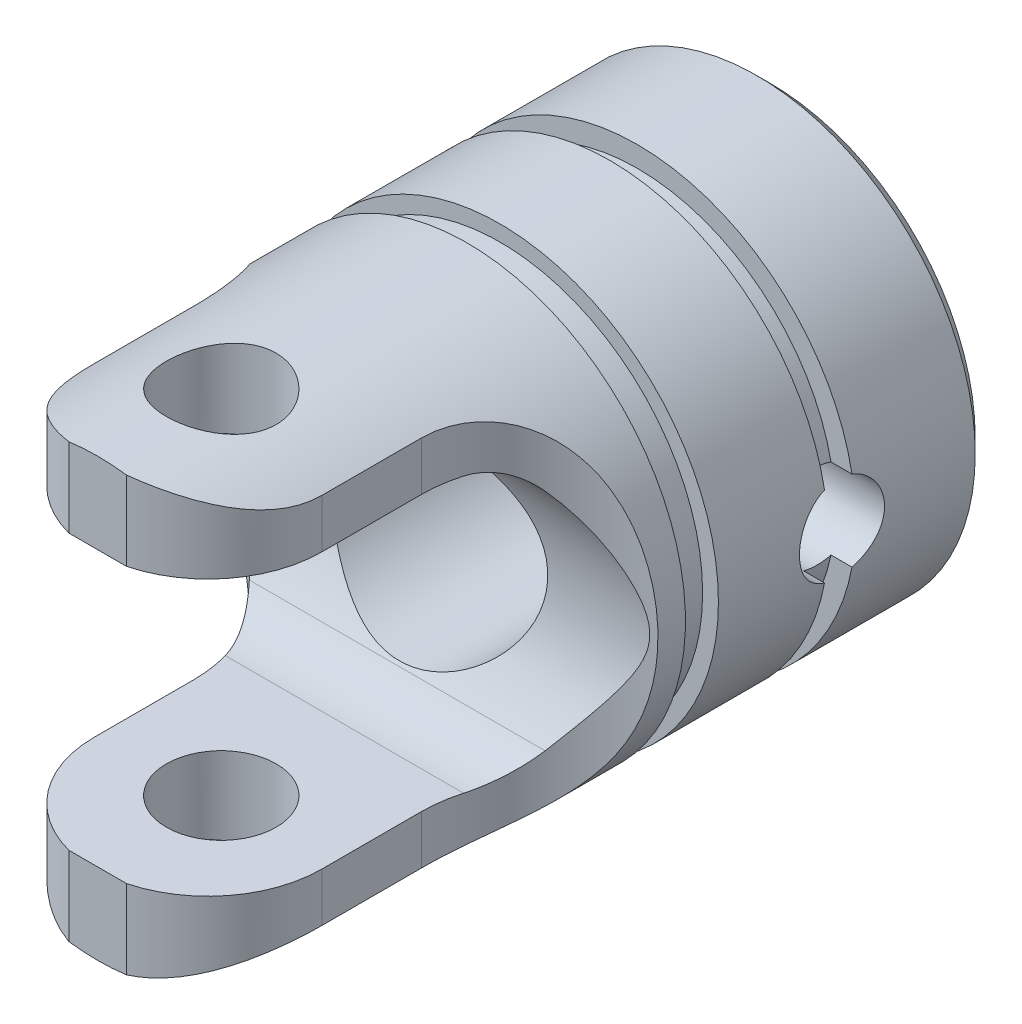
SolidWorks part; units mm, degrees
material "AISI 1020"
ref_plane "Front Plane" through (0, 0, 0) normal (0, 0, 1) x (1, 0, 0)
ref_plane "Top Plane" through (0, 0, 0) normal (0, 1, 0) x (1, 0, 0)
ref_plane "Right Plane" through (0, 0, 0) normal (1, 0, 0) x (0, 0, -1)
sketch "Sketch1" plane through (0, 0, 0) normal (0, 0, 1) x (1, 0, 0)
  circle A1 centre (0, 0) radius 15.9
  dimension "D1" = 31.8
extrude "Boss-Extrude1" add sketch "Sketch1" along normal blind 49 contours A1
sketch "Sketch2" plane through (0, 0, 0) normal (0, 0, 1) x (1, 0, 0)
  circle A0 centre (0, 0) radius 8
extrude "Cut-Extrude1" cut sketch "Sketch2" along normal blind 49
sketch "Sketch3" plane through (0, 0, 0) normal (1, 0, 0) x (0, 0, -1)
  line L3 (0, 17.545) -> (0, -17.545) construction
  circle A1 centre (-10.7, 0) radius 3.1
  dimension "D1" = 10.7
  dimension "D2" = 6.2
extrude "Cut-Extrude2" cut sketch "Sketch3" against normal through all both and the other way through all
sketch "Sketch4" plane through (0, 0, 0) normal (0, 1, 0) x (1, 0, 0)
  line L0 (15.9, -7.6) -> (15.9, -13.8) construction
  line L2 (14.4, -9.7) -> (17.4, -9.7)
  line L3 (14.4, -9.7) -> (14.4, -11.7)
  line L4 (14.4, -11.7) -> (17.4, -11.7)
  line L5 (17.4, -9.7) -> (17.4, -11.7)
  line L6 (14.4, -9.7) -> (17.4, -11.7) construction
  line L7 (14.4, -11.7) -> (17.4, -9.7) construction
  point P4 (15.9, -10.7)
  point P9 (14.4, -10.7)
  dimension "D1" = 1
  dimension "D2" = 1.5
sketch "Sketch6" plane through (0, 0, 0) normal (0, 1, 0) x (1, 0, 0)
  line L0 (0, -49) -> (0, 0) construction
  line L1 (-15.9, -49) -> (15.9, -49) construction
  line L4 (14.4, -9.7) -> (17.4, -9.7)
  line L5 (14.4, -9.7) -> (14.4, -11.7)
  line L6 (14.4, -11.7) -> (17.4, -11.7)
  line L7 (17.4, -9.7) -> (17.4, -11.7)
  line L8 (14.4, -9.7) -> (17.4, -11.7) construction
  line L9 (14.4, -11.7) -> (17.4, -9.7) construction
  point P7 (15.9, -10.7)
revolve "Cut-Revolve2" cut sketch "Sketch6" angle 360 about L0
sketch "Sketch7" plane through (0, 0, 0) normal (0, 1, 0) x (1, 0, 0)
  line L0 (15.9, -49) -> (15.9, -13.8) construction
  line L1 (17.05, -19.7) -> (14.75, -19.7)
  line L2 (17.05, -19.7) -> (17.05, -22.1)
  line L3 (17.05, -22.1) -> (14.75, -22.1)
  line L4 (14.75, -19.7) -> (14.75, -22.1)
  line L5 (17.05, -19.7) -> (14.75, -22.1) construction
  line L6 (17.05, -22.1) -> (14.75, -19.7) construction
  line L7 (14.4, -11.7) -> (17.4, -11.7) construction
  line L9 (0, 0) -> (0, -49) construction
  line L10 (-15.9, -49) -> (15.9, -49) construction
  point P0 (15.9, -20.9)
  point P9 (17.05, -20.9)
  dimension "D1" = 8
  dimension "D2" = 2.4
  dimension "D3" = 2.3
revolve "Cut-Revolve3" cut sketch "Sketch7" angle 360 about L9
sketch "Sketch8" plane through (0, 0, 0) normal (0, 1, 0) x (1, 0, 0)
  line L0 (15.9, -24.1) -> (15.9, -43.3622)
  line L1 (15.9, -49) -> (15.9, -22.1) construction
  line L4 (8.3, -40.9701) -> (8.3, -33.7311)
  line L5 (-15.9, -24.1) -> (-15.9, -50.3727)
  line L6 (-15.9, -50.3727) -> (15.9, -50.3727)
  line L7 (15.9, -50.3727) -> (15.9, -43.3622)
  line L8 (-8.3, -40.9701) -> (-8.3, -33.7311)
  arc A0 (15.9, -24.1) -> (8.3, -33.7311) centre (18.2025, -33.7311) ccw
  arc A1 (-15.9, -24.1) -> (-8.3, -33.7311) centre (-18.2025, -33.7311) cw
  arc A2 (-8.3, -40.9701) -> (8.3, -40.9701) centre (0, -40.9701) ccw
extrude "Cut-Extrude3" cut sketch "Sketch8" against normal through all both and the other way through all
sketch "Sketch9" plane through (0, 0, 0) normal (1, 0, 0) x (0, 0, -1)
  line L0 (12, 3.5063) -> (12, -7.637)
  line L1 (-49.0568, 10) -> (-49.0251, -10)
  line L2 (-49.0568, 10) -> (-29.0568, 10)
  line L3 (-49.0251, -10) -> (-29.0251, -10)
  arc A1 (-29.0251, -10) -> (-29.0568, 10) centre (-37.0158, -0.0126) ccw
  point P5 (-49.0409, 0)
  dimension "D4" = 12.7906
  dimension "D1" = 20
  dimension "D2" = 20
  dimension "D3" = 20
extrude "Cut-Extrude4" cut sketch "Sketch9" against normal through all both and the other way through all contours L3 A1 L2 L1
chamfer "Chamfer1" distance 1 angle 45 2 edges at (8, 0, 0) (15.9, 0, 0)
sketch "Sketch10" plane through (0, -10, 0) normal (0, 1, 0) x (1, 0, 0)
  line L0 (0, -17.49) -> (0, 17.49) construction
  line L1 (-2.1, -49) -> (2.1, -49) construction
  circle A0 centre (0, -40) radius 4
  dimension "D1" = 8
  dimension "D2" = 9
extrude "Cut-Extrude5" cut sketch "Sketch10" against normal through all both and the other way through all
fillet "Fillet2" radius 5 2 edges at (0, -10, 29.0251) (0, 10, 29.0568)
sketch "Sketch11" plane through (0, 0, 0) normal (0, 1, 0) x (1, 0, 0)
  line L0 (15.9, -10.7) -> (-15.9996, -10.7) construction
